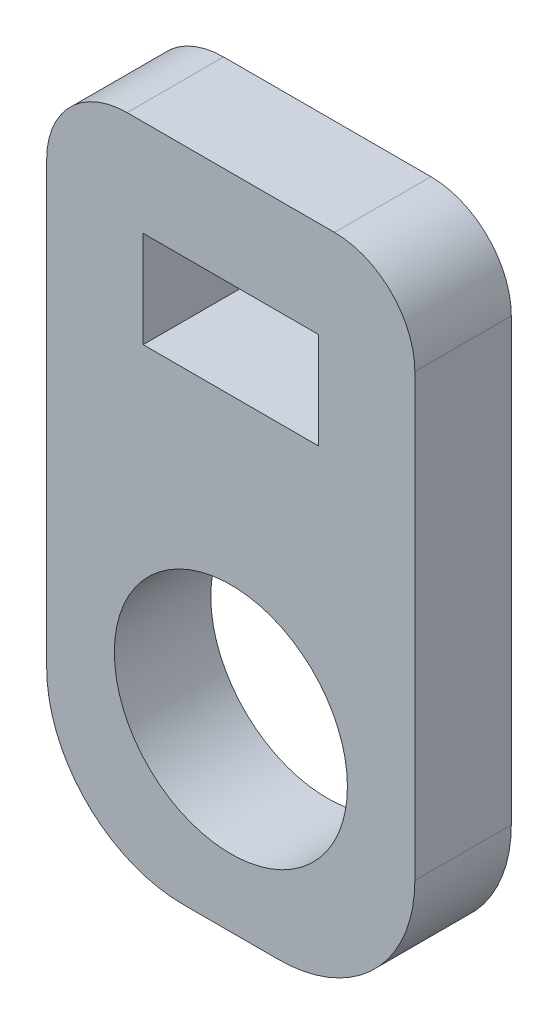
SolidWorks part; units mm, degrees
ref_plane "Front Plane" through (0, 0, 0) normal (0, 0, 1) x (1, 0, 0)
ref_plane "Top Plane" through (0, 0, 0) normal (0, 1, 0) x (1, 0, 0)
ref_plane "Right Plane" through (0, 0, 0) normal (1, 0, 0) x (0, 0, -1)
sketch "Sketch1" plane through (0, 0, 0) normal (0, 0, 1) x (1, 0, 0)
  line L1 (0, 0) -> (58.166, 0)
  line L2 (0, 0) -> (0, 103.92)
  line L3 (0, 103.92) -> (58.166, 103.92)
  line L4 (58.166, 0) -> (58.166, 103.92)
  dimension "D1" = 103.92
  dimension "D2" = 58.166
extrude "Boss-Extrude1" add sketch "Sketch1" along normal blind 15.24
sketch "Sketch2" plane through (0, 0, 15.24) normal (0, 0, 1) x (1, 0, 0)
  line L0 (0, 58.2) -> (58.166, 58.2) construction
  line L1 (0, 103.92) -> (0, 0) construction
  line L2 (58.166, 0) -> (58.166, 103.92) construction
  line L4 (15.24, 88.68) -> (42.926, 88.68)
  line L5 (15.24, 88.68) -> (15.24, 73.44)
  line L6 (15.24, 73.44) -> (42.926, 73.44)
  line L7 (42.926, 88.68) -> (42.926, 73.44)
  line L8 (0, 81.06) -> (15.24, 81.06) construction
  line L9 (42.926, 81.06) -> (58.166, 81.06) construction
  dimension "D1" = 45.72
  dimension "D2" = 15.24
  dimension "D4" = 15.24
  dimension "D3" = 15.24
  dimension "D5" = 27.686
sketch "Sketch4" plane through (0, 0, 15.24) normal (0, 0, 1) x (1, 0, 0)
extrude "Cut-Extrude1" cut sketch "Sketch2" against normal through all
sketch "Sketch7" plane through (0, 0, 15.24) normal (0, 0, 1) x (1, 0, 0)
  line L0 (0, 0) -> (58.166, 0) construction
  line L1 (0, 103.92) -> (0, 0) construction
  circle A0 centre (29.1, 29.1) radius 18.415
  dimension "D1" = 36.83
  dimension "D2" = 29.1
  dimension "D3" = 29.1
extrude "Cut-Extrude2" cut sketch "Sketch7" against normal through all and the other way through all
sketch "Sketch8" plane through (0, 0, 15.24) normal (0, 0, 1) x (1, 0, 0)
  line L0 (0, 58.2) -> (58.166, 58.2) construction
  line L1 (0, 103.92) -> (0, 0) construction
  line L2 (58.166, 0) -> (58.166, 103.92) construction
  line L3 (58.166, 103.92) -> (0, 103.92) construction
  dimension "D1" = 45.72
fillet "Fillet2" radius 21.59 2 edges at (58.166, 0, 7.62) (0, 0, 7.62)
fillet "Fillet3" radius 12.7 2 edges at (0, 103.92, 7.62) (58.166, 103.92, 7.62)
equation "\"MDF\"= .3"
equation "\"Foamcore\"= .1"
equation "\"GMaterial\"= .6"
equation "\"CutDistance\" = .1"
equation "\"D1@Boss-Extrude1\"=\"GMaterial\""
equation "\"D1@Sketch1\"=3*\"GMaterial\" + 58.2mm"
equation "\"D1@Sketch2\"=3*\"GMaterial\""
equation "\"D2@Sketch2\"=\"GMaterial\""
equation "\"D4@Sketch2\"=\"GMaterial\""
equation "\"D1@Sketch8\"=\"GMaterial\" * 3"
